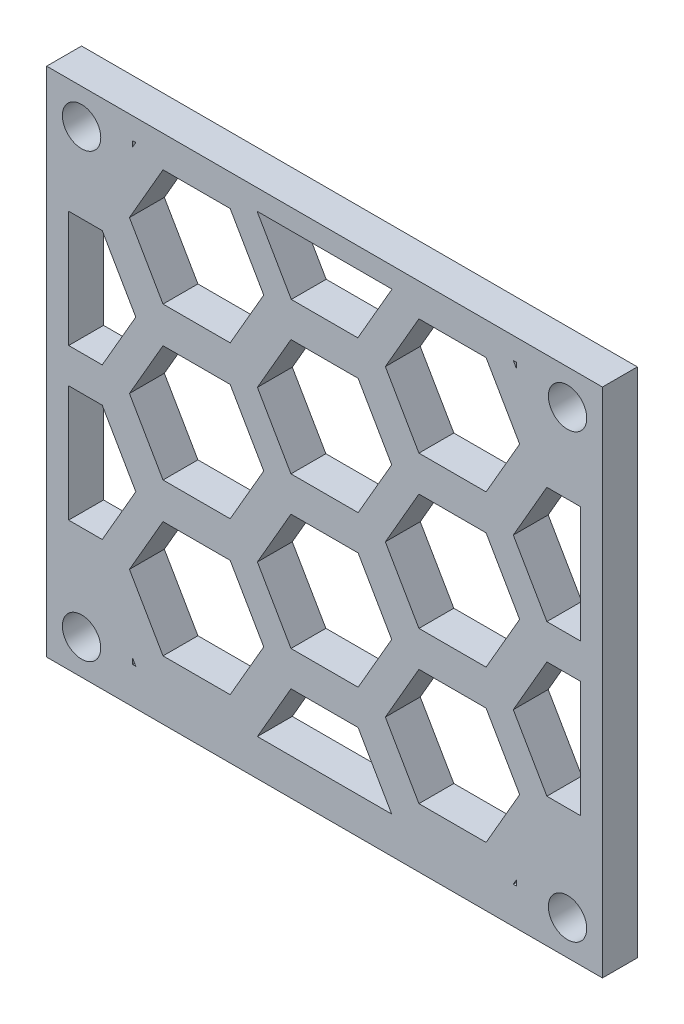
SolidWorks part; units mm, degrees
ref_plane "Plano frontal" through (0, 0, 0) normal (0, 0, 1) x (1, 0, 0)
ref_plane "Plano superior" through (0, 0, 0) normal (0, 1, 0) x (1, 0, 0)
ref_plane "Plano direito" through (0, 0, 0) normal (1, 0, 0) x (0, 0, -1)
sketch "Esboço1" plane through (0, 0, 0) normal (0, 0, 1) x (1, 0, 0)
  line L0 (-5.2265, 28.0441) -> (-8.1132, 33.0441)
  line L1 (-8.1132, 33.0441) -> (-13.8868, 33.0441)
  line L2 (-13.8868, 33.0441) -> (-16.7735, 28.0441)
  line L161 (-11, 48) -> (-11, 2) construction
  line L162 (-5.2265, 14.9474) -> (-8.1132, 19.9474)
  line L163 (-8.1132, 19.9474) -> (-13.8868, 19.9474)
  line L171 (-13.8868, 19.9474) -> (-16.7735, 14.9474)
  line L172 (-16.7735, 14.9474) -> (-13.8868, 9.9474)
  line L173 (-13.8868, 9.9474) -> (-8.1132, 9.9474)
  line L186 (-8.1132, 9.9474) -> (-5.2265, 14.9474)
  line L189 (0, 48.8543) -> (0, 4.8543) construction
  line L198 (11, 48) -> (11, 2) construction
  line L225 (2.8868, 13) -> (-2.8868, 13)
  line L226 (-2.8868, 13) -> (-5.7735, 8)
  line L242 (5.7735, 8) -> (2.8868, 13)
  line L255 (-16.7735, 28.0441) -> (-13.8868, 23.0441)
  line L256 (-13.8868, 23.0441) -> (-8.1132, 23.0441)
  line L257 (-8.1132, 23.0441) -> (-5.2265, 28.0441)
  line L258 (-5.2265, 41.1407) -> (-8.1132, 46.1407)
  line L259 (-8.1132, 46.1407) -> (-13.8868, 46.1407)
  line L260 (-13.8868, 46.1407) -> (-16.7735, 41.1407)
  line L261 (-16.7735, 41.1407) -> (-13.8868, 36.1407)
  line L262 (-13.8868, 36.1407) -> (-8.1132, 36.1407)
  line L263 (-8.1132, 36.1407) -> (-5.2265, 41.1407)
  line L264 (2.8868, 26) -> (-2.8868, 26)
  line L265 (-2.8868, 26) -> (-5.7735, 21)
  line L266 (-5.7735, 21) -> (-2.8868, 16)
  line L267 (-2.8868, 16) -> (2.8868, 16)
  line L268 (2.8868, 16) -> (5.7735, 21)
  line L269 (5.7735, 21) -> (2.8868, 26)
  line L270 (2.8868, 39) -> (-2.8868, 39)
  line L271 (-2.8868, 39) -> (-5.7735, 34)
  line L272 (-5.7735, 34) -> (-2.8868, 29)
  line L273 (-2.8868, 29) -> (2.8868, 29)
  line L274 (2.8868, 29) -> (5.7735, 34)
  line L275 (5.7735, 34) -> (2.8868, 39)
  line L276 (16.7735, 27.9958) -> (13.8868, 32.9958)
  line L277 (16.7735, 14.9474) -> (13.8868, 19.9474)
  line L278 (13.8868, 19.9474) -> (8.1132, 19.9474)
  line L279 (8.1132, 19.9474) -> (5.2265, 14.9474)
  line L280 (5.2265, 14.9474) -> (8.1132, 9.9474)
  line L281 (8.1132, 9.9474) -> (13.8868, 9.9474)
  line L282 (13.8868, 9.9474) -> (16.7735, 14.9474)
  line L283 (13.8868, 32.9958) -> (8.1132, 32.9958)
  line L284 (8.1132, 32.9958) -> (5.2265, 27.9958)
  line L285 (5.2265, 27.9958) -> (8.1132, 22.9958)
  line L286 (8.1132, 22.9958) -> (13.8868, 22.9958)
  line L287 (13.8868, 22.9958) -> (16.7735, 27.9958)
  line L288 (16.7735, 41.0441) -> (13.8868, 46.0441)
  line L289 (13.8868, 46.0441) -> (8.1132, 46.0441)
  line L290 (8.1132, 46.0441) -> (5.2265, 41.0441)
  line L291 (5.2265, 41.0441) -> (8.1132, 36.0441)
  line L292 (8.1132, 36.0441) -> (13.8868, 36.0441)
  line L293 (13.8868, 36.0441) -> (16.7735, 41.0441)
  line L296 (-22, 48.8543) -> (-22, 4.8543) construction
  line L297 (22, 48.8543) -> (22, 4.8543) construction
  line L298 (-22, 13) -> (-22, 8)
  line L299 (-16.2265, 8) -> (-19.1132, 13)
  line L300 (-19.1132, 13) -> (-22, 13)
  line L305 (-22, 16) -> (-19.1132, 16)
  line L306 (-22, 48.8543) -> (22, 48.8543)
  line L307 (-22, 48.8543) -> (-22, 4.8543)
  line L308 (-19.1132, 16) -> (-16.2265, 21)
  line L309 (-16.2265, 21) -> (-19.1132, 26)
  line L310 (-19.1132, 26) -> (-22, 26)
  line L311 (-22, 26) -> (-22, 16)
  line L312 (-22, 29) -> (-19.1132, 29)
  line L313 (-19.1132, 29) -> (-16.2265, 34)
  line L314 (-16.2265, 34) -> (-19.1132, 39)
  line L315 (-19.1132, 39) -> (-22, 39)
  line L316 (-22, 39) -> (-22, 29)
  line L317 (-22, 42) -> (-19.1132, 42)
  line L318 (-19.1132, 42) -> (-16.2265, 47)
  line L321 (-22, 47) -> (-22, 42)
  line L322 (-16.2265, 47) -> (-22, 47)
  line L323 (16.2265, 8) -> (22, 8)
  line L324 (-22, 4.8543) -> (22, 4.8543)
  line L325 (22, 48.8543) -> (22, 4.8543)
  line L333 (-16.2265, 8) -> (-22, 8)
  line L335 (22, 13) -> (19.1132, 13)
  line L357 (-5.8014, 47.0966) -> (5.8014, 47.0966)
  line L361 (-5.8014, 47.0966) -> (-2.8589, 42)
  line L362 (-2.8589, 42) -> (2.8589, 42)
  line L363 (2.8589, 42) -> (5.8014, 47.0966)
  line L365 (-22, 48.8543) -> (-23.89, 48.8543)
  line L366 (-22, 48.8543) -> (-22, 4.8543)
  line L367 (-22, 4.8543) -> (-23.89, 4.8543)
  line L371 (19.1132, 13) -> (16.2265, 8)
  line L375 (22, 8) -> (22, 13)
  line L376 (22, 26) -> (22, 16)
  line L393 (-23.89, 48.8543) -> (-23.89, 4.8543)
  line L394 (22, 48.8543) -> (23.89, 48.8543)
  line L396 (22, 48.8543) -> (22, 4.8543)
  line L397 (22, 4.8543) -> (23.89, 4.8543)
  line L398 (22, 26) -> (19.1132, 26)
  line L399 (19.1132, 26) -> (16.2265, 21)
  line L400 (16.2265, 21) -> (19.1132, 16)
  line L401 (23.89, 48.8543) -> (23.89, 4.8543)
  line L403 (19.1132, 16) -> (22, 16)
  line L407 (16.2265, 34) -> (19.1132, 29)
  line L408 (19.1132, 29) -> (22, 29)
  line L409 (22, 39) -> (22, 29)
  line L416 (22, 39) -> (19.1132, 39)
  line L417 (19.1132, 39) -> (16.2265, 34)
  line L418 (16.2265, 47) -> (19.1132, 42)
  line L419 (19.1132, 42) -> (22, 42)
  line L420 (22, 47) -> (22, 42)
  line L423 (16.2265, 47) -> (22, 47)
  line L424 (-5.7735, 8) -> (5.7735, 8)
  line L431 (-26.3301, 10.5) -> (-27.7735, 8) [skipped]
  line L432 (-26.3301, 5.5) -> (-24.8868, 3) [skipped]
  line L433 (-19.1132, 52) -> (-22, 52) [skipped]
  line L434 (-16.2265, 47) -> (-19.1132, 52) [skipped]
  line L435 (2.8868, 51.9034) -> (0, 51.9034) [skipped]
  line L436 (5.7107, 46.9638) -> (4.2674, 49.4638) [skipped]
  line L437 (-4.2674, 49.4638) -> (-5.7107, 46.9638) [skipped]
  line L438 (-19.1132, 3) -> (-17.6699, 5.5) [skipped]
  line L439 (-22, 3) -> (-19.1132, 3) [skipped]
  line L440 (17.6699, 5.5) -> (19.1132, 3) [skipped]
  line L441 (22, 3) -> (24.8868, 3) [skipped]
  line L442 (26.3301, 5.5) -> (27.7735, 8) [skipped]
  line L443 (26.3301, 10.5) -> (24.8868, 13) [skipped]
  line L444 (27.7735, 21) -> (26.3301, 23.5) [skipped]
  line L445 (24.8868, 16) -> (26.3301, 18.5) [skipped]
  line L446 (22, 52) -> (19.1132, 52) [skipped]
  line L447 (19.1132, 52) -> (16.2265, 47) [skipped]
  line L448 (2.8868, 3) -> (4.3301, 5.5) [skipped]
  line L449 (-2.8868, 3) -> (0, 3) [skipped]
  line L450 (-5.7735, 8) -> (-4.3301, 5.5) [skipped]
  circle A0 centre (-11, 14.9474) radius 5 construction
  arc A1 (5, 8) -> (-5, 8) centre (0, 8) ccw construction
  circle A2 centre (11, 14.9474) radius 5 construction
  arc A3 (-17, 8) -> (-22, 13) centre (-22, 8) ccw construction
  arc A4 (22, 13) -> (17, 8) centre (22, 8) ccw construction
  arc A5 (22, 26) -> (22, 16) centre (22, 21) ccw construction
  arc A6 (-4.9979, 47.0966) -> (4.9979, 47.0966) centre (0, 46.9517) ccw construction
  point P18 (0, 13)
  dimension "D3" = 11
  dimension "D2" = 3
  dimension "D4" = 3
  dimension "D6" = 10
  dimension "D8" = 3
  dimension "D10" = 3
  dimension "D13" = 4
  dimension "D16" = 3
  dimension "D19" = 3
  dimension "D20" = 3
  dimension "D1" = 10
  dimension "D5" = 3
  dimension "D9" = 10
  dimension "D11" = 5
  dimension "D14" = 10
  dimension "D18" = 10
  dimension "D15" = 10
  dimension "D7" = 3
  dimension "D12" = 3
  dimension "D17" = 47.78
  dimension "D22" = 3
  dimension "D21" = 44
extrude "Ressalto-extrusão2" add sketch "Esboço1" along normal blind 3 contours L365 L393 L367 L307 L298 | L418 L423 L325 L306 L307 L322 L318 L317 L315 L314 L313 L312 L310 L309 L308 L305 L300 L299 L333 L324 L323 L371 L335 L403 L400 L399 L398 L396 L408 L407 L417 L416 L419 L424 L226 L225 L242 L363 L362 L361 L357 | L401 L394 L325 L396 L397
sketch "Esboço2" plane through (0, 0, 3) normal (0, 0, 1) x (1, 0, 0)
  line L0 (23.89, 48.8543) -> (-23.89, 48.8543) construction
  line L1 (-22.5, 48.8543) -> (22.5, 48.8543)
  line L2 (-22.5, 48.8543) -> (-22.5, 42)
  line L3 (-22.5, 42) -> (22.5, 42)
  line L4 (22.5, 48.8543) -> (22.5, 42)
  line L5 (-22.5, 48.8543) -> (22.5, 42) construction
  line L6 (-22.5, 42) -> (22.5, 48.8543) construction
  line L7 (23.89, 4.8543) -> (-23.89, 4.8543) construction
  line L8 (-22.5, 4.8543) -> (22.5, 4.8543)
  line L9 (-22.5, 4.8543) -> (-22.5, 13)
  line L10 (-22.5, 13) -> (22.5, 13)
  line L11 (22.5, 4.8543) -> (22.5, 13)
  line L12 (-22.5, 4.8543) -> (22.5, 13) construction
  line L13 (-22.5, 13) -> (22.5, 4.8543) construction
  line L14 (-16.2265, 47) -> (-22, 47) construction
  line L16 (16.2265, 8) -> (22, 8) construction
  line L17 (-5.8014, 47.0966) -> (5.8014, 47.0966) construction
  line L18 (-16.5, 42) -> (16.5, 42)
  line L19 (-16.5, 42) -> (-16.5, 47.0966)
  line L20 (-16.5, 47.0966) -> (16.5, 47.0966)
  line L21 (16.5, 42) -> (16.5, 47.0966)
  line L22 (-16.5, 13) -> (16.5, 13)
  line L23 (-16.5, 13) -> (-16.5, 8)
  line L24 (-16.5, 8) -> (16.5, 8)
  line L25 (16.5, 13) -> (16.5, 8)
  line L26 (-5.7735, 8) -> (5.7735, 8) construction
  point P0 (0, 45.4271)
  point P9 (0, 8.9271)
  point P27 (0, 47.0966)
  point P28 (0, 8)
  dimension "D1" = 5
  dimension "D2" = 45
  dimension "D3" = 5
  dimension "D4" = 45
  dimension "D5" = 6
  dimension "D6" = 6
extrude "Ressalto-extrusão3" add sketch "Esboço2" against normal up to surface (3 mm away) contours L21 L3 L4 L1 L2 L19 L20 | L10 L25 L24 L23 L9 L8 L11 up to face at (19.8349, 44.5, 0)
sketch "Esboço4" plane through (0, 0, 3) normal (0, 0, 1) x (1, 0, 0)
  line L3 (0, -1.65) -> (0, 1.65) construction
  line L5 (-23.89, 48.8543) -> (-23.89, 4.8543) construction
  line L6 (23.89, 48.8543) -> (-23.89, 48.8543) construction
  line L7 (23.89, 4.8543) -> (-23.89, 4.8543) construction
  circle A0 centre (-20.89, 45.8543) radius 1.65
  circle A1 centre (-20.89, 7.8543) radius 1.65
  circle A2 centre (20.89, 7.8543) radius 1.65
  circle A3 centre (20.89, 45.8543) radius 1.65
  point P4 (0, 0)
  point P8 (0, 0)
  dimension "D1" = 3.3
  dimension "D2" = 3
  dimension "D3" = 3
  dimension "D4" = 3
  dimension "D5" = 3
extrude "Corte-extrusão2" cut sketch "Esboço4" against normal through all
